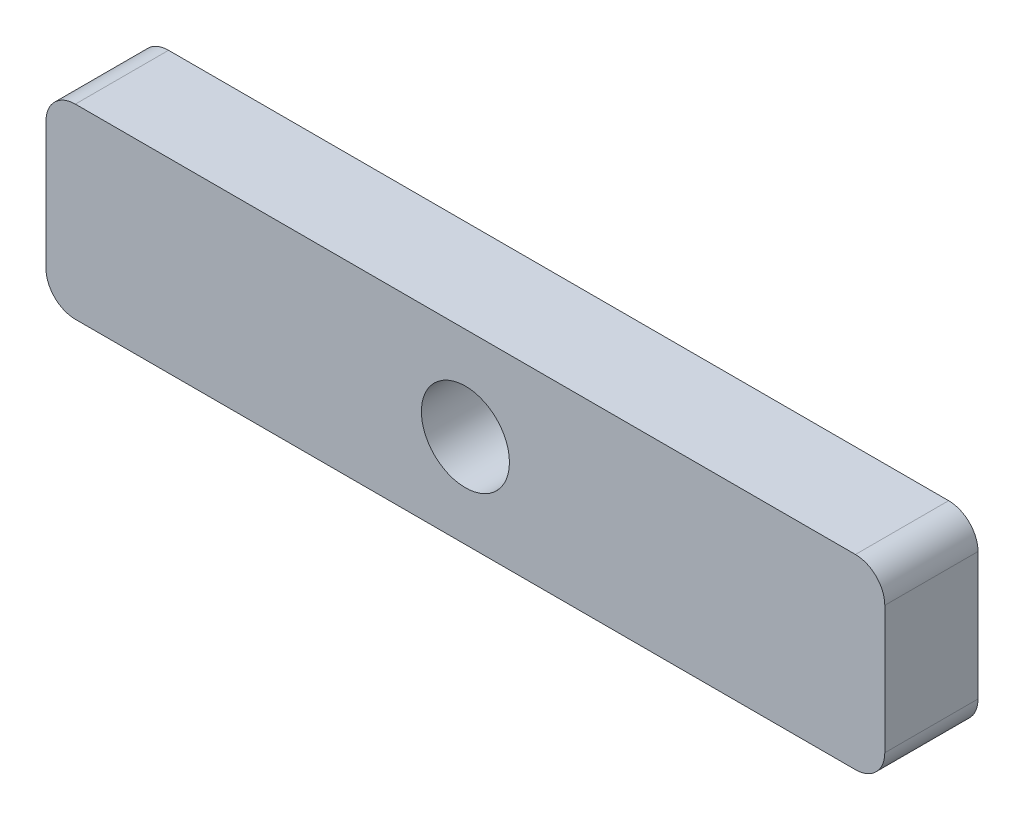
SolidWorks part; units mm, degrees
material "Custom Plastic"
ref_plane "X-Y Datum" through (0, 0, 0) normal (0, 0, 1) x (1, 0, 0)
ref_plane "X-Z Datum" through (0, 0, 0) normal (0, 1, 0) x (1, 0, 0)
ref_plane "Y-Z Datum" through (0, 0, 0) normal (1, 0, 0) x (0, 0, -1)
sketch "Sketch1" plane through (0, 0, 0) normal (0, 0, 1) x (1, 0, 0)
  line L1 (-28.575, -6.35) -> (28.575, -6.35)
  line L2 (-28.575, -6.35) -> (-28.575, 6.35)
  line L3 (-28.575, 6.35) -> (28.575, 6.35)
  line L4 (28.575, -6.35) -> (28.575, 6.35)
  line L5 (-28.575, -6.35) -> (28.575, 6.35) construction
  line L6 (-28.575, 6.35) -> (28.575, -6.35) construction
  circle A0 centre (0, 0) radius 3
  point P0 (0, 0)
  dimension "D1" = 6
extrude "Boss-Extrude1" add sketch "Sketch1" along normal blind 6.35
fillet "Fillet1" radius 2 4 edges at (28.575, 6.35, 3.175) (28.575, -6.35, 3.175) (-28.575, -6.35, 3.175) (-28.575, 6.35, 3.175)
